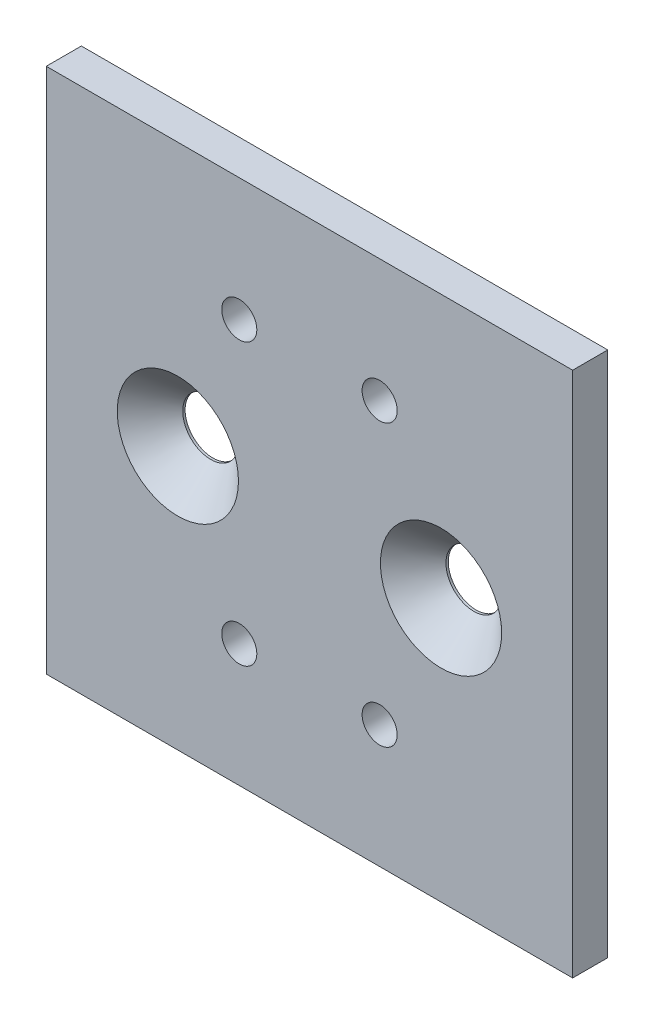
SolidWorks part; units mm, degrees
ref_plane "Front Plane" through (0, 0, 0) normal (0, 0, 1) x (1, 0, 0)
ref_plane "Top Plane" through (0, 0, 0) normal (0, 1, 0) x (1, 0, 0)
ref_plane "Right Plane" through (0, 0, 0) normal (1, 0, 0) x (0, 0, -1)
sketch "Sketch1" plane through (0, 0, 0) normal (0, 0, 1) x (1, 0, 0)
  line L0 (0, 0) -> (0, 60)
  line L1 (15, 30) -> (45, 30) construction
  line L4 (60, 60) -> (0, 60)
  line L5 (60, 0) -> (0, 0)
  line L7 (60, 60) -> (60, 0)
  circle A0 centre (15, 30) radius 3.175
  circle A1 centre (45, 30) radius 3.175
  dimension "D1" = 30
  dimension "E" = 6.35
  dimension "D2" = 15
  dimension "C" = 60
  dimension "D3" = 30
  dimension "B" = 60
extrude "Boss-Extrude1" add sketch "Sketch1" along normal mid plane 4
sketch "Sketch2" plane through (0, 0, 2) normal (0, 0, 1) x (1, 0, 0)
  circle A1 centre (15, 30) radius 6.9088
  circle A3 centre (45, 30) radius 6.9088
  dimension "CSK" = 13.8176
extrude "Cut-Extrude1" cut sketch "Sketch2" against normal through all draft 45
sketch "Sketch3" plane through (0, 0, 2) normal (0, 0, 1) x (1, 0, 0)
  line L2 (30, 60) -> (30, 0) construction
  line L3 (60, 60) -> (0, 60) construction
  line L4 (0, 0) -> (60, 0) construction
  line L5 (60, 0) -> (60, 60) construction
  line L6 (0, 60) -> (0, 0) construction
  line L7 (0, 30) -> (60, 30) construction
  circle A3 centre (22, 14) radius 2
  circle A4 centre (38, 14) radius 2
  circle A5 centre (38, 46) radius 2
  circle A6 centre (22, 46) radius 2
  dimension "D1" = 4
extrude "Cut-Extrude2" cut sketch "Sketch3" against normal through all
